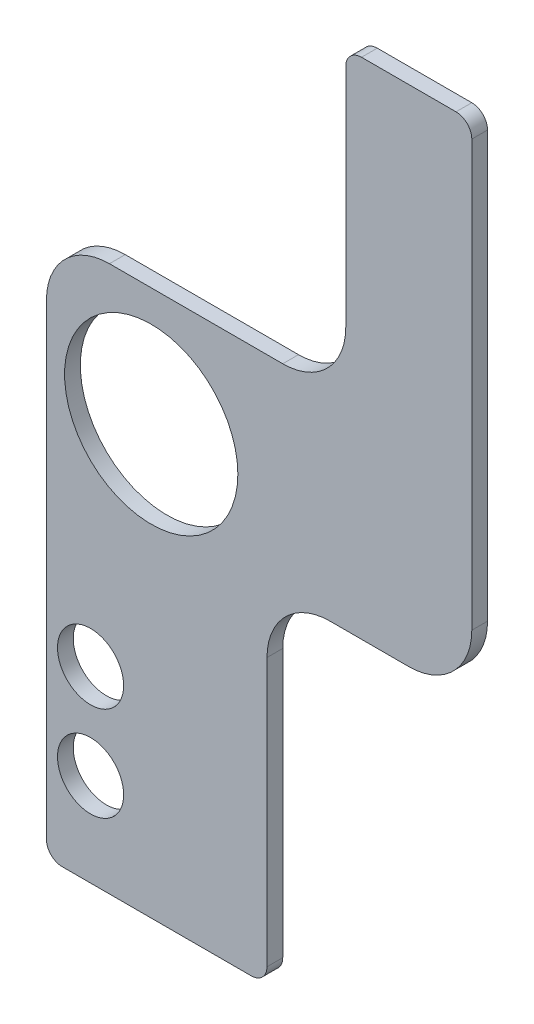
SolidWorks part; units mm, degrees
ref_plane "Front Plane" through (0, 0, 0) normal (0, 0, 1) x (1, 0, 0)
ref_plane "Top Plane" through (0, 0, 0) normal (0, 1, 0) x (1, 0, 0)
ref_plane "Right Plane" through (0, 0, 0) normal (1, 0, 0) x (0, 0, -1)
sketch "Sketch2" plane through (0, 0, 0) normal (0, 0, 1) x (1, 0, 0)
  line L0 (4.8232, -0.4885) -> (9.8232, -0.4885)
  line L1 (-12.1768, -22.4885) -> (-0.1768, -22.4885)
  line L2 (-13.1768, -21.4885) -> (-13.1768, 8.1615)
  line L4 (0.8232, -21.4885) -> (0.8232, -4.4885)
  line L5 (6.8232, 31.5115) -> (12.8232, 31.5115)
  line L6 (13.8232, 3.5115) -> (13.8232, 30.5115)
  line L7 (-9.1768, 12.1615) -> (1.8232, 12.1615)
  line L8 (5.8232, 16.1615) -> (5.8232, 30.5115)
  circle A2 centre (-10.3768, -16.5885) radius 2.1
  circle A3 centre (-10.3768, -10.5885) radius 2.1
  arc A4 (0.8232, -4.4885) -> (4.8232, -0.4885) centre (4.8232, -4.4885) cw
  arc A5 (9.8232, -0.4885) -> (13.8232, 3.5115) centre (9.8232, 3.5115) ccw
  arc A6 (-13.1768, 8.1615) -> (-9.1768, 12.1615) centre (-9.1768, 8.1615) cw
  arc A7 (5.8232, 16.1615) -> (1.8232, 12.1615) centre (1.8232, 16.1615) cw
  arc A8 (13.8232, 30.5115) -> (12.8232, 31.5115) centre (12.8232, 30.5115) ccw
  arc A9 (6.8232, 31.5115) -> (5.8232, 30.5115) centre (6.8232, 30.5115) ccw
  arc A10 (0.8232, -21.4885) -> (-0.1768, -22.4885) centre (-0.1768, -21.4885) cw
  arc A11 (-12.1768, -22.4885) -> (-13.1768, -21.4885) centre (-12.1768, -21.4885) cw
  circle A13 centre (-6.5268, 4.6615) radius 5.5
  point P29 (0, 0)
  point P31 (0, 0)
  point P32 (-6.6421, 5.3795)
  dimension "D1" = 4.2
  dimension "D2" = 4
  dimension "D3" = 4
  dimension "D4" = 1
  dimension "D5" = 11
  dimension "D6" = 21.25
  dimension "D7" = 6
  dimension "D8" = 3.85
  dimension "D9" = 2.8
  dimension "D10" = 5.9
  dimension "D11" = 14
  dimension "D12" = 22
  dimension "D13" = 13
  dimension "D14" = 7.5
  dimension "D15" = 8
  dimension "D16" = 32
extrude "Boss-Extrude1" add sketch "Sketch2" along normal blind 1
